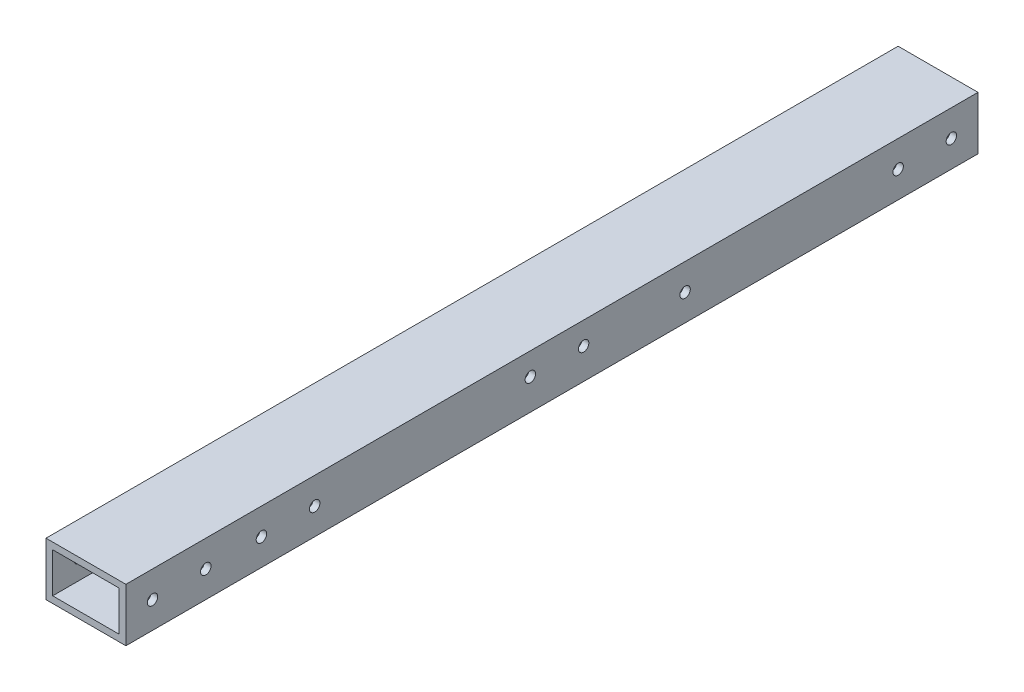
SolidWorks part; units mm, degrees
material "1060 Alloy"
ref_plane "Front Plane" through (0, 0, 0) normal (0, 0, 1) x (1, 0, 0)
ref_plane "Top Plane" through (0, 0, 0) normal (0, 1, 0) x (1, 0, 0)
ref_plane "Right Plane" through (0, 0, 0) normal (1, 0, 0) x (0, 0, -1)
sketch "Sketch1" plane through (0, 0, 0) normal (0, 0, 1) x (1, 0, 0)
  line L0 (-15.875, 9.525) -> (15.875, 9.525)
  line L2 (-19.05, 12.7) -> (19.05, 12.7)
  line L3 (-19.05, 12.7) -> (-19.05, -12.7)
  line L4 (-19.05, -12.7) -> (19.05, -12.7)
  line L5 (19.05, 12.7) -> (19.05, -12.7)
  line L10 (15.875, 9.525) -> (15.875, -9.525)
  line L11 (-15.875, -9.525) -> (15.875, -9.525)
  line L12 (-15.875, 9.525) -> (-15.875, -9.525)
  point P12 (0, 12.7)
  point P14 (19.05, 0)
  dimension "Wall Thickness" = 3.175
  dimension "Outside Width" = 38.1
  dimension "Outside Height" = 25.4
  dimension "Inside Height" = 19.05
  dimension "Inside Width" = 31.75
sketch "Sketch2" plane through (0, 0, 0) normal (1, 0, 0) x (0, 0, -1)
  line L0 (317.5, 0) -> (-317.5, 0)
  point P4 (0, 0)
  point P7 (-317.5, 0)
  point P10 (317.5, 0)
  dimension "Length" = 635
sketch "Sketch3" plane through (0, 0, 0) normal (0, 0, 1) x (1, 0, 0)
  line L21 (19.05, 12.7) -> (-19.05, 12.7)
  line L22 (19.05, -12.7) -> (19.05, 12.7)
  line L23 (-19.05, -12.7) -> (19.05, -12.7)
  line L24 (-19.05, 12.7) -> (-19.05, -12.7)
  line L25 (19.05, 12.7) -> (-19.05, 12.7)
  line L26 (19.05, -12.7) -> (19.05, 12.7)
  line L27 (-19.05, -12.7) -> (19.05, -12.7)
  line L28 (-19.05, 12.7) -> (-19.05, -12.7)
  line L29 (15.875, 9.525) -> (-15.875, 9.525)
  line L30 (15.875, -9.525) -> (15.875, 9.525)
  line L31 (-15.875, -9.525) -> (15.875, -9.525)
  line L32 (-15.875, 9.525) -> (-15.875, -9.525)
  line L33 (15.875, 9.525) -> (-15.875, 9.525)
  line L34 (15.875, -9.525) -> (15.875, 9.525)
  line L35 (-15.875, -9.525) -> (15.875, -9.525)
  line L36 (-15.875, 9.525) -> (-15.875, -9.525)
  dimension "D1" = 0
  dimension "D2" = 0
extrude "Boss-Extrude1" add sketch "Sketch3" along normal up to vertex (317.5 mm away) and the other way up to vertex (317.5 mm away) up to point (0, 0, 317.5) other way up to point (0, 0, -317.5)
sketch "Drawing Reference" plane through (0, 0, 0) normal (1, 0, 0) x (0, 0, -1)
  line L0 (-317.5, 0) -> (317.5, 0) construction
  line L1 (0, -12.7) -> (0, 12.7) construction
  line L2 (-317.5, -12.7) -> (317.5, -12.7) construction
  line L5 (-317.5, 12.7) -> (317.5, 12.7) construction
  point P7 (-290.068, 0)
  point P8 (290.068, 0)
  dimension "D1" = 27.432
sketch "Sketch4" plane through (-19.05, 0, 0) normal (-1, 0, 0) x (0, 0, 1)
  line L3 (317.5, 12.7) -> (317.5, -12.7) construction
  line L4 (317.5, 0) -> (304.8, 0)
  line L5 (304.8, 0) -> (279.4, 0)
  line L6 (0, 0) -> (50.8, 0) construction
  line L7 (0, 0) -> (-50.8, 0) construction
  line L8 (-50.8, 0) -> (-76.2, 0) construction
  point P14 (304.8, 0)
  point P15 (279.4, 0)
hole_wizard "#10 Clearance Hole2" positions "Sketch11" profile "Sketch12" hole size "#10" standard "ANSI Inch" end condition through all
sketch "Sketch11" plane through (-19.05, 0, 0) normal (-1, 0, 0) x (0, 0, 1)
  point P6 (279.4, 0)
  point P9 (304.8, 0)
  point P12 (-76.2, 0)
sketch "Sketch12" plane through (-19.05, 0, 279.4) normal (0, 1, 0) x (0, 0, 1)
  line L0 (0, 0) -> (0, 38.1)
  line L1 (0, 38.1) -> (2.4892, 38.1)
  line L2 (2.4892, 38.1) -> (2.4892, 0)
  line L5 (2.4892, 0) -> (0, 0)
  line L11 (0, -6.35) -> (0, 107.95) construction
  dimension "Thru Hole Dia." = 4.9784
  dimension "Thru Hole Depth" = 38.1
hole_wizard "#10 Clearance Hole4" positions "Sketch14" profile "Sketch16" hole size "#10" standard "ANSI Inch" end condition through all
sketch "Sketch14" plane through (19.05, 0, 0) normal (1, 0, 0) x (0, 0, -1)
  point P33 (-252.857, 0)
  point P36 (-227.457, 0)
  point P42 (-124.587, 1.9434)
  point P45 (-99.187, 1.9434)
sketch "Sketch16" plane through (19.05, 0, 252.857) normal (0, 1, 0) x (0, 0, -1)
  line L0 (0, 0) -> (0, 38.1)
  line L1 (0, 38.1) -> (2.4892, 38.1)
  line L2 (2.4892, 38.1) -> (2.4892, 0)
  line L5 (2.4892, 0) -> (0, 0)
  line L11 (0, -6.35) -> (0, 107.95) construction
  dimension "Thru Hole Dia." = 4.9784
  dimension "Thru Hole Depth" = 38.1
hole_wizard "#10 Clearance Hole3" positions "Sketch20" profile "Sketch21" hole size "#10" standard "ANSI Inch" end condition through all
sketch "Sketch20" plane through (-19.05, 0, 0) normal (-1, 0, 0) x (0, 0, 1)
  point P0 (-50.8, 0)
  point P3 (50.8, 0)
sketch "Sketch21" plane through (-19.05, 0, -50.8) normal (0, 1, 0) x (0, 0, 1)
  line L0 (0, 0) -> (0, 38.1)
  line L1 (0, 38.1) -> (2.4892, 38.1)
  line L2 (2.4892, 38.1) -> (2.4892, 0)
  line L5 (2.4892, 0) -> (0, 0)
  line L11 (0, -6.35) -> (0, 107.95) construction
  dimension "Thru Hole Dia." = 4.9784
  dimension "Thru Hole Depth" = 38.1
ref_plane "Plane1" through (0, 0, -88.9) normal (0, 0, -1) x (-1, 0, 0)
other "SurfaceCut1"
equation "\"D1@Drawing Reference\"=\"Outside Width@Sketch1\" * 0.72"
